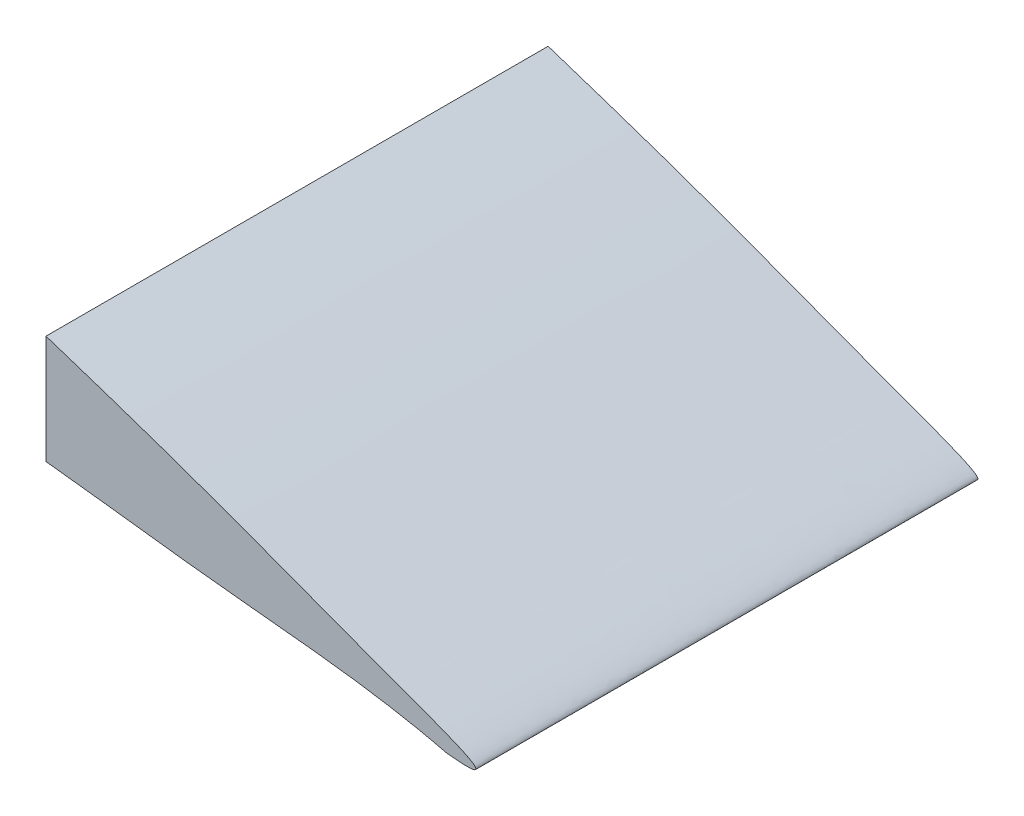
SolidWorks part; units mm, degrees
ref_plane "Front Plane" through (0, 0, 0) normal (0, 0, 1) x (1, 0, 0)
ref_plane "Top Plane" through (0, 0, 0) normal (0, 1, 0) x (1, 0, 0)
ref_plane "Right Plane" through (0, 0, 0) normal (1, 0, 0) x (0, 0, -1)
sketch "Sketch1" plane through (0, 0, 0) normal (0, 0, 1) x (1, 0, 0)
  spline S0 degree 3 poles (0.0006, 0.0001) (0.8106, 7.3592) (8.6491, 17.8566) (26.2867, 29.9752) (52.1111, 42.0692) (89.5976, 49.2908) (131.4008, 47.8848) (173.2567, 40.0411) (217.9611, 29.613) (256.9521, 19.5289) (290.3598, 8.711) (301.2732, 4.3828) (314.8169, -0.5162) (309.8463, 0.0001) knots 0 0 0 0 0.060864 0.113688 0.188609 0.312909 0.448482 0.557612 0.691544 0.852438 0.929756 0.976058 1 1 1 1
  spline S1 degree 3 poles (309.8463, 0.0001) (303.9568, 1.471) (293.9895, 2.094) (276.264, 4.5144) (260.8463, 5.4274) (235.8588, 7.8703) (205.1014, 8.8381) (157.7186, 9.0307) (110.4973, 6.1815) (66.5062, -0.5867) (36.4547, -6.0985) (15.3166, -6.1891) (1.2307, -6.9241) (0.0006, 0.0001) knots 0 0 0 0 0.057787 0.095275 0.171021 0.205339 0.335319 0.464904 0.658702 0.785512 0.893517 0.943092 1 1 1 1
extrude "Boss-Extrude1" add sketch "Sketch1" along normal blind 38.1
sketch "Sketch2" plane through (0, 0, 38.1) normal (0, 0, 1) x (1, 0, 0)
  circle A0 centre (20.32, 10.16) radius 6.35
  circle A1 centre (227.2963, 19.0501) radius 3.175
  dimension "D2" = 12.7
  dimension "D3" = 6.35
  dimension "D6" = 20.32
  dimension "D1" = 82.55
  dimension "D4" = 19.05
  dimension "D5" = 10.16
extrude "Cut-Extrude1" cut sketch "Sketch2" against normal through all
sketch "Sketch4" plane through (0, 0, 38.1) normal (0, 0, 1) x (1, 0, 0)
  line L1 (279.4006, -24.2166) -> (-9.3155, -24.2166)
  line L2 (279.4006, -24.2166) -> (279.4006, 93.2727)
  line L3 (279.4006, 93.2727) -> (-9.3155, 93.2727)
  line L4 (-9.3155, -24.2166) -> (-9.3155, 93.2727)
  dimension "D1" = 279.4
extrude "Cut-Extrude3" cut sketch "Sketch4" against normal through all
